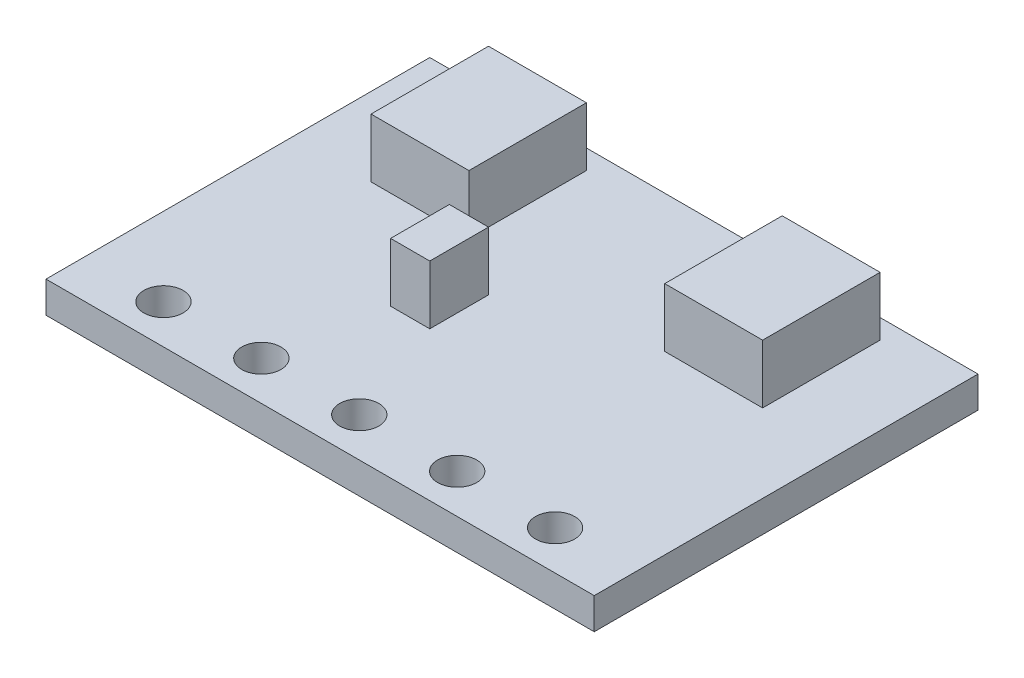
SolidWorks part; units mm, degrees
material "PPE"
ref_plane "Front Plane" through (0, 0, 0) normal (0, 0, 1) x (1, 0, 0)
ref_plane "Top Plane" through (0, 0, 0) normal (0, 1, 0) x (1, 0, 0)
ref_plane "Right Plane" through (0, 0, 0) normal (1, 0, 0) x (0, 0, -1)
sketch "Sketch1" plane through (0, 0, 0) normal (0, 1, 0) x (1, 0, 0)
  line L1 (-7, -4.9) -> (7, -4.9)
  line L2 (-7, -4.9) -> (-7, 4.9)
  line L3 (-7, 4.9) -> (7, 4.9)
  line L4 (7, -4.9) -> (7, 4.9)
  line L5 (-7, -4.9) -> (7, 4.9) construction
  line L6 (-7, 4.9) -> (7, -4.9) construction
  point P0 (0, 0)
  dimension "D1" = 14
  dimension "D2" = 9.8
extrude "Boss-Extrude1" add sketch "Sketch1" along normal blind 3.3
sketch "Sketch2" plane through (0, 3.3, 0) normal (0, 1, 0) x (1, 0, 0)
  line L5 (-7, 4.9) -> (-7, -4.9) construction
  line L6 (-5, 1.4) -> (-2.5, 1.4)
  line L11 (-5, 1.4) -> (-5, 4.4)
  line L12 (-5, 4.4) -> (-2.5, 4.4)
  line L17 (-2.5, 1.4) -> (-2.5, 4.4)
  line L18 (-5, 1.4) -> (-2.5, 4.4) construction
  line L21 (-5, 4.4) -> (-2.5, 1.4) construction
  line L22 (2.5, 1.4) -> (5, 1.4)
  line L23 (2.5, 1.4) -> (2.5, 4.4)
  line L24 (2.5, 4.4) -> (5, 4.4)
  line L25 (5, 1.4) -> (5, 4.4)
  line L26 (2.5, 1.4) -> (5, 4.4) construction
  line L27 (2.5, 4.4) -> (5, 1.4) construction
  line L28 (-2, -1.1) -> (-1, -1.1)
  line L29 (-2, -1.1) -> (-2, 0.4)
  line L30 (-2, 0.4) -> (-1, 0.4)
  line L31 (-1, -1.1) -> (-1, 0.4)
  line L32 (-2, -1.1) -> (-1, 0.4) construction
  line L33 (-2, 0.4) -> (-1, -1.1) construction
  line L34 (7, -4.9) -> (7, 4.9) construction
  line L35 (7, 4.9) -> (-7, 4.9) construction
  point P0 (-3.75, 2.9)
  point P5 (3.75, 2.9)
  point P10 (-1.5, -0.35)
  point P19 (0, 0)
  point P22 (-1.1372, -0.8748)
  line M12 (7, -4.9) -> (7, 4.9)
  line M13 (7, 4.9) -> (-7, 4.9)
  line M14 (-7, 4.9) -> (-7, -4.9)
  line M15 (-7, -4.9) -> (7, -4.9)
  dimension "D1" = 2
  dimension "D2" = 2
  dimension "D3" = 2.5
  dimension "D4" = 3
  dimension "D5" = 3
  dimension "D6" = 2.5
  dimension "D7" = 0.5
  dimension "D8" = 0.5
  dimension "D9" = 1
  dimension "D10" = 1
  dimension "D11" = 1.5
extrude "Cut-Extrude1" cut sketch "Sketch2" against normal blind 1.5 contours L6 L17 L12 L11 L22 L25 L24 L23 L28 L31 L30 L29 M15 M12 M13 M14
sketch "Sketch3" plane through (0, 0, 0) normal (0, -1, 0) x (1, 0, 0)
  line L5 (7, -4.9) -> (-7, -4.9) construction
  line L6 (-6.5, -0.4) -> (-5.5, -0.4)
  line L8 (-6.5, -0.4) -> (-6.5, -2.4)
  line L9 (-6.5, -2.4) -> (-5.5, -2.4)
  line L10 (-5.5, -0.4) -> (-5.5, -2.4)
  line L11 (-6.5, -0.4) -> (-5.5, -2.4) construction
  line L12 (-6.5, -2.4) -> (-5.5, -0.4) construction
  line L13 (-7, -4.9) -> (-7, 4.9) construction
  point P0 (-6, -1.4)
  line M5 (7, -4.9) -> (7, 4.9)
  line M6 (7, 4.9) -> (-7, 4.9)
  line M7 (-7, 4.9) -> (-7, -4.9)
  line M8 (-7, -4.9) -> (7, -4.9)
  dimension "D1" = 2.5
  dimension "D2" = 1
  dimension "D3" = 2
  dimension "D4" = 0.5
extrude "Cut-Extrude2" cut sketch "Sketch3" against normal blind 1 contours L10 L6 L8 L9 M8 M5 M6 M7
sketch "Sketch4" plane through (0, 1, 0) normal (0, -1, 0) x (1, 0, 0)
  line L0 (-7, 4.9) -> (-7, -4.9) construction
  line L1 (7, -4.9) -> (7, 4.9) construction
  line L2 (7, 4.9) -> (-7, 4.9) construction
  circle A0 centre (-5, 3.9) radius 0.5
  circle A1 centre (-2.5, 3.9) radius 0.5
  circle A2 centre (0, 3.9) radius 0.5
  circle A3 centre (2.5, 3.9) radius 0.5
  circle A4 centre (5, 3.9) radius 0.5
  point P10 (0, 0)
  dimension "D2" = 1
  dimension "D1" = 2
  dimension "D3" = 2
  dimension "D4" = 2.5
  dimension "D5" = 2.5
  dimension "D6" = 2.5
  dimension "D7" = 1
extrude "Cut-Extrude3" cut sketch "Sketch4" against normal blind 1
